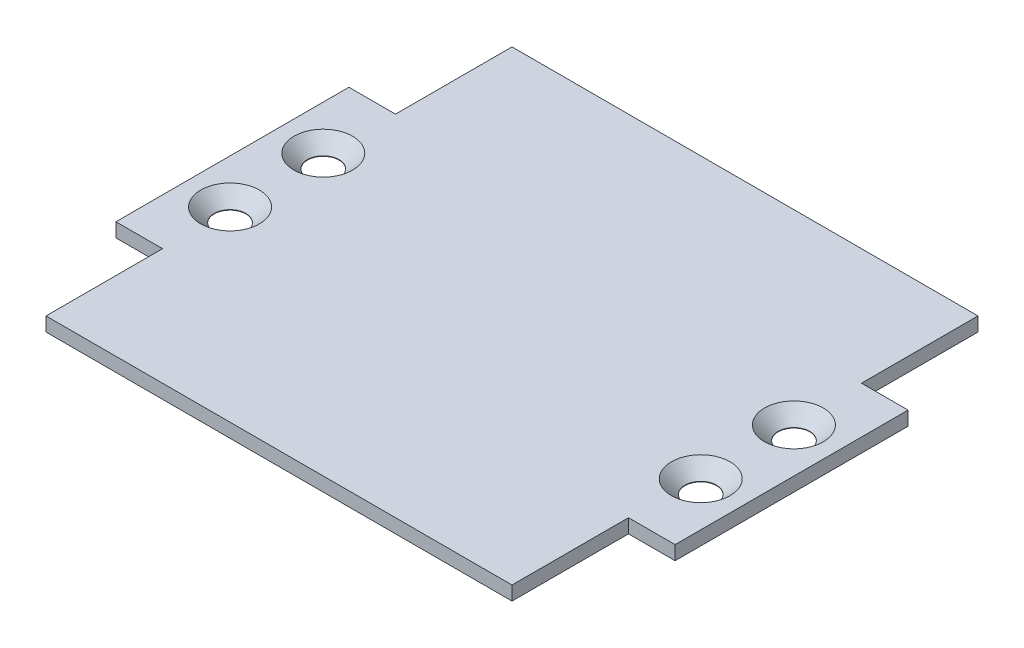
SolidWorks part; units mm, degrees
material "ABS"
ref_plane "Front Plane" through (0, 0, 0) normal (0, 0, 1) x (1, 0, 0)
ref_plane "Top Plane" through (0, 0, 0) normal (0, 1, 0) x (1, 0, 0)
ref_plane "Right Plane" through (0, 0, 0) normal (1, 0, 0) x (0, 0, -1)
sketch "Sketch1" plane through (0, 0, 0) normal (0, 1, 0) x (1, 0, 0)
  line L1 (-12.5, 25) -> (12.5, 25)
  line L2 (-12.5, 25) -> (-12.5, -25)
  line L3 (-12.5, -25) -> (12.5, -25)
  line L4 (12.5, 25) -> (12.5, -25)
  line L5 (-12.5, 25) -> (12.5, -25) construction
  line L6 (-12.5, -25) -> (12.5, 25) construction
  line L7 (17.5, -12.5) -> (12.5, -12.5)
  line L8 (17.5, -12.5) -> (17.5, 12.5)
  line L9 (17.5, 12.5) -> (12.5, 12.5)
  line L10 (12.5, -12.5) -> (12.5, 12.5)
  line L11 (17.5, -12.5) -> (12.5, 12.5) construction
  line L12 (17.5, 12.5) -> (12.5, -12.5) construction
  line L13 (-12.5, -25) -> (-37.5, -25)
  line L14 (-12.5, -25) -> (-12.5, 25)
  line L15 (-12.5, 25) -> (-37.5, 25)
  line L16 (-37.5, -25) -> (-37.5, 25)
  line L17 (-37.5, 12.5) -> (-42.5, 12.5)
  line L18 (-37.5, 12.5) -> (-37.5, -12.5)
  line L19 (-37.5, -12.5) -> (-42.5, -12.5)
  line L20 (-42.5, 12.5) -> (-42.5, -12.5)
  point P0 (0, 0)
  point P8 (15, 0)
  dimension "D3" = 5
  dimension "D1" = 50
  dimension "D2" = 25
  dimension "D4" = 5
  dimension "D5" = 25
  dimension "D6" = 12.5
  dimension "D7" = 25
  dimension "D8" = 25
  dimension "D9" = 12.5
extrude "Boss-Extrude1" add sketch "Sketch1" along normal blind 1.5
sketch "Sketch2" plane through (0, 1.5, 0) normal (0, 1, 0) x (1, 0, 0)
  line L0 (-42.5, 12.5) -> (-42.5, -12.5) construction
  line L1 (17.5, 12.5) -> (12.5, 12.5) construction
  line L2 (-37.5, 12.5) -> (-42.5, 12.5) construction
  line L3 (-37.5, -12.5) -> (-42.5, -12.5) construction
  line L4 (17.5, -12.5) -> (12.5, -12.5) construction
  line L5 (17.5, -12.5) -> (17.5, 12.5) construction
  point P0 (12.75, -5)
  point P1 (12.75, 5)
  point P8 (-37.75, 5)
  point P9 (-37.75, -5)
  dimension "D1" = 4.75
  dimension "D2" = 7.5
  dimension "D3" = 7.5
  dimension "D4" = 4.75
  dimension "D5" = 4.75
  dimension "D6" = 4.75
  dimension "D7" = 7.5
  dimension "D8" = 7.5
hole_wizard "CSK for M3 Countersunk Flat Head Screw1" positions "3DSketch1" profile "Sketch3" countersink size "M3" standard "ISO" end condition through all
sketch3d "3DSketch1"
  point P0 (12.75, 1.5, 5)
  point P3 (12.75, 1.5, -5)
  point P6 (-37.75, 1.5, -5)
  point P9 (-37.75, 1.5, 5)
sketch "Sketch3" plane through (12.75, 1.5, 5) normal (1, 0, 0) x (0, 0, 1)
  line L0 (0, 0) -> (0, 1.5)
  line L1 (0, 1.5) -> (1.7, 1.5)
  line L2 (1.7, 1.5) -> (1.7, 1.45)
  line L3 (1.7, 1.45) -> (3.15, 0)
  line L5 (3.15, 0) -> (0, 0)
  line L6 (-1.7, 1.45) -> (-3.15, 0) construction
  line L11 (0, -6.35) -> (0, 107.95) construction
  dimension "Thru Hole Dia." = 3.4
  dimension "Thru Hole Depth" = 1.5
  dimension "Near C'Sink Dia." = 6.3
  dimension "Near C'Sink Angle" = 90
